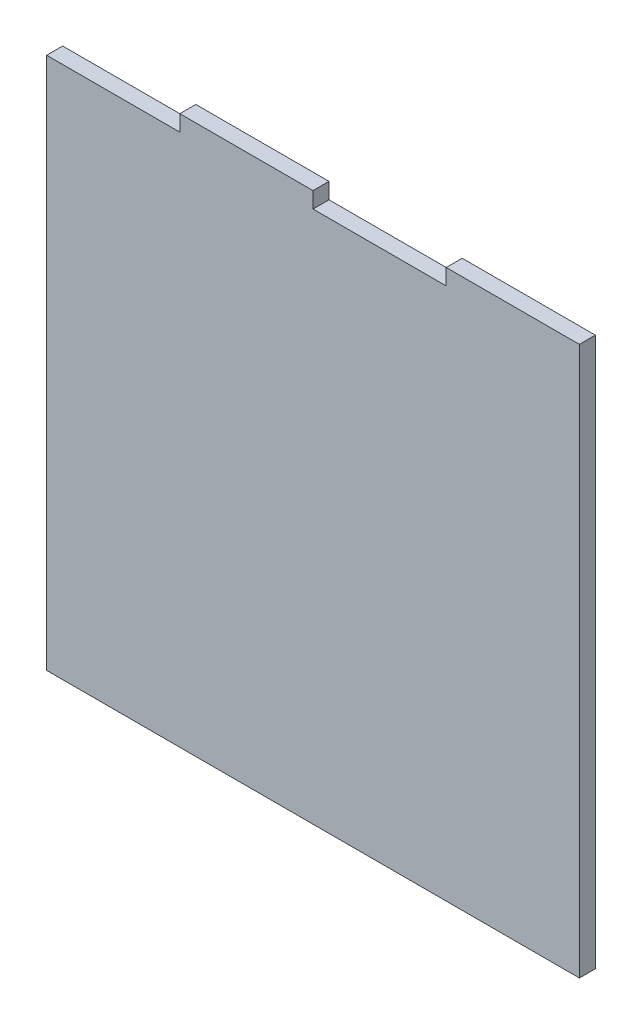
SolidWorks part; units mm, degrees
material "Perspex (TM) Plaque acrylique coulée"
ref_plane "Plan de face" through (0, 0, 0) normal (0, 0, 1) x (1, 0, 0)
ref_plane "Plan de dessus" through (0, 0, 0) normal (0, 1, 0) x (1, 0, 0)
ref_plane "Plan de droite" through (0, 0, 0) normal (1, 0, 0) x (0, 0, -1)
sketch "Esquisse1" plane through (0, 0, 0) normal (0, 0, 1) x (1, 0, 0)
  line L0 (0, 0) -> (50, 0)
  line L2 (0, 0) -> (0, -200)
  line L3 (0, -200) -> (200, -200)
  line L4 (200, 0) -> (200, -200)
  line L5 (50, 0) -> (50, 6)
  line L6 (50, 6) -> (100, 6)
  line L7 (100, 6) -> (100, 0)
  line L8 (100, 0) -> (150, 0)
  line L9 (150, 0) -> (150, 6)
  line L10 (150, 6) -> (200, 6)
  line L11 (200, 6) -> (200, 0)
  dimension "D1" = 200
  dimension "20" = 200
  dimension "D2" = 0
  dimension "D3" = 50
  dimension "D4" = 6
  dimension "D5" = 50
  dimension "D6" = 6
  dimension "D7" = 50
  dimension "D8" = 6
extrude "Boss.-Extru.1" add sketch "Esquisse1" along normal blind 6
